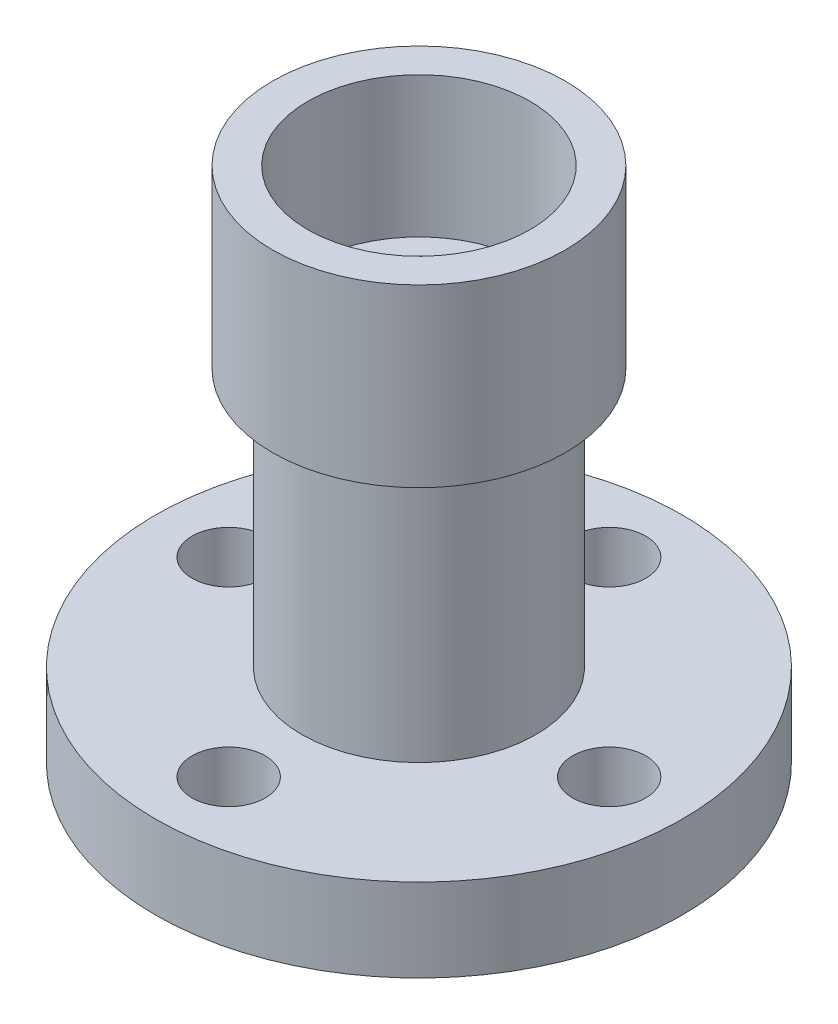
SolidWorks part; units mm, degrees
ref_plane "Alzado" through (0, 0, 0) normal (0, 0, 1) x (1, 0, 0)
ref_plane "Planta" through (0, 0, 0) normal (0, 1, 0) x (1, 0, 0)
ref_plane "Vista lateral" through (0, 0, 0) normal (1, 0, 0) x (0, 0, -1)
sketch "Croquis2" plane through (0, 0, 0) normal (0, 1, 0) x (1, 0, 0)
  circle A0 centre (0, 0) radius 45
  dimension "D1" = 90
extrude "Saliente-Extruir1" add sketch "Croquis2" along normal blind 14.2
sketch "Croquis3" plane through (0, 0, 0) normal (0, 1, 0) x (1, 0, 0)
  circle A0 centre (0, 0) radius 20
  circle A1 centre (0, 0) radius 15
  dimension "D1" = 40
  dimension "D2" = 30
extrude "Saliente-Extruir3" add sketch "Croquis3" along normal blind 77.4 contours A0
ref_plane "Plano2" through (0, 58.4, 0) normal (0, 1, 0) x (1, 0, 0)
sketch "Croquis7" plane through (0, 58.4, 0) normal (0, 1, 0) x (1, 0, 0)
  circle A0 centre (0, 0) radius 25
  dimension "D1" = 50
extrude "Saliente-Extruir5" add sketch "Croquis7" along normal blind 30
sketch "Croquis9" plane through (0, 58.4, 0) normal (0, 1, 0) x (1, 0, 0)
  circle A0 centre (0, 0) radius 19
  dimension "D1" = 38
sketch "Croquis13" plane through (0, 0, 0) normal (0, 1, 0) x (1, 0, 0)
  circle A1 centre (0, 0) radius 15
  dimension "D2" = 30
extrude "Cortar-Extruir4" cut sketch "Croquis13" along normal blind 64.4
chamfer "Chaflán1" distance 3 distance2 3.5 1 edges at (0, 0, 15)
sketch "Croquis14" plane through (0, 88.4, 0) normal (0, 1, 0) x (1, 0, 0)
  circle A0 centre (0, 0) radius 19
extrude "Cortar-Extruir5" cut sketch "Croquis14" against normal blind 24
sketch "Croquis15" plane through (0, 14.2, 0) normal (0, 1, 0) x (1, 0, 0)
  line L0 (0, 0) -> (0, -32.5) construction
  circle A0 centre (0, -32.5) radius 6.25
  circle A1 centre (-32.5, 0) radius 6.25
  circle A2 centre (0, 32.5) radius 6.25
  circle A3 centre (32.5, 0) radius 6.25
  point P13 (0, 0)
  dimension "D2" = 12.5
  dimension "D1" = 32.5
  dimension "D3" = 4
extrude "Cortar-Extruir6" cut sketch "Croquis15" against normal blind 14.2
